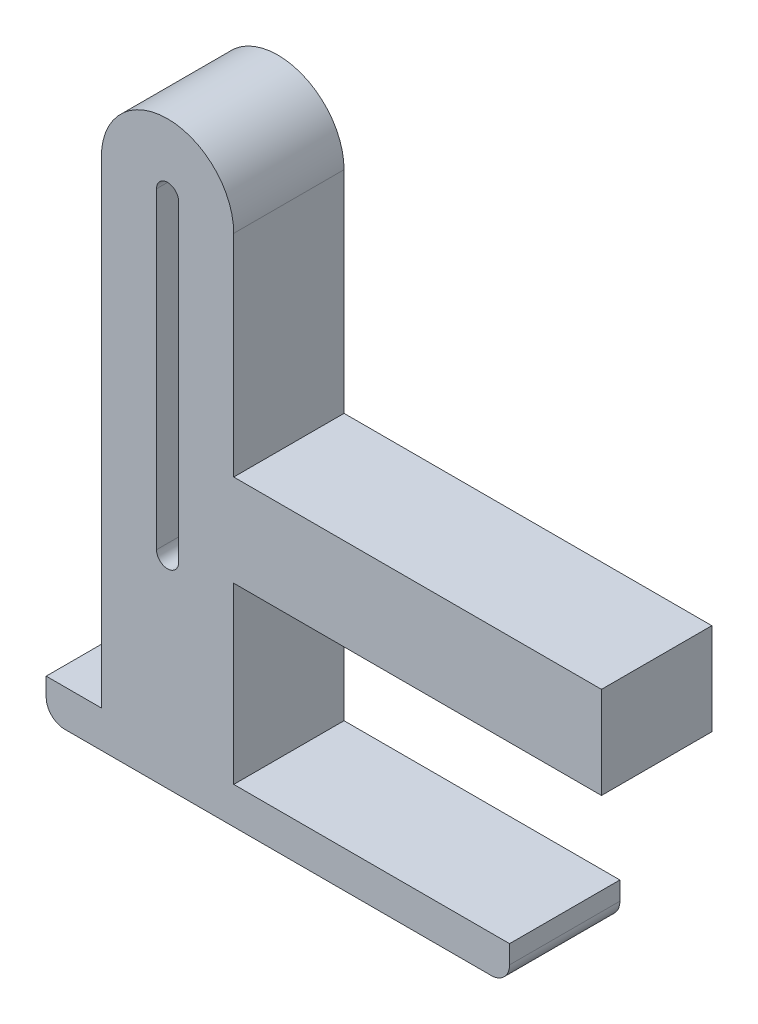
SolidWorks part; units mm, degrees
ref_plane "Front Plane" through (0, 0, 0) normal (0, 0, 1) x (1, 0, 0)
ref_plane "Top Plane" through (0, 0, 0) normal (0, 1, 0) x (1, 0, 0)
ref_plane "Right Plane" through (0, 0, 0) normal (1, 0, 0) x (0, 0, -1)
sketch "Sketch1" plane through (0, 0, 0) normal (0, 0, 1) x (1, 0, 0)
  line L0 (0, 0) -> (0, 17) construction
  line L1 (-0.6, 0) -> (-0.6, 17)
  line L2 (0.6, 0) -> (0.6, 17)
  line L3 (-3.6, 0) -> (-3.6, 17)
  line L4 (3.6, 0) -> (3.6, 17)
  line L5 (-3.6, 0) -> (3.6, 0) construction
  line L6 (3.6, 0) -> (3.6, -10.9543)
  line L7 (3.6, -10.9543) -> (-3.6, -10.9543)
  line L8 (-3.6, -10.9543) -> (-3.6, 0)
  arc A0 (-0.6, 0) -> (0.6, 0) centre (0, 0) ccw
  arc A1 (0.6, 17) -> (-0.6, 17) centre (0, 17) ccw
  arc A2 (3.6, 17) -> (-3.6, 17) centre (0, 17) ccw
  point P2 (0, 8.5)
  dimension "D2" = 10.9543
  dimension "D3" = 3.6
  dimension "D5" = 0.6
  dimension "D1" = 3
  dimension "D4" = 17
extrude "Boss-Extrude1" add sketch "Sketch1" along normal blind 6
sketch "Sketch2" plane through (3.6, 0, 0) normal (1, 0, 0) x (0, 0, -1)
  line L0 (-3, 17) -> (-3, -10.9543) construction
  line L1 (-6, 17) -> (0, 17) construction
  line L3 (-6, 3.0228) -> (0, 3.0228) construction
  line L4 (-6, -10.9543) -> (-6, 17) construction
  line L5 (0, -10.9543) -> (0, 17) construction
  line L6 (-6, -10.9543) -> (0, -10.9543) construction
  line L7 (-6, 0.5228) -> (0, 0.5228)
  line L8 (-6, 0.5228) -> (-6, 5.5228)
  line L9 (-6, 5.5228) -> (0, 5.5228)
  line L10 (0, 0.5228) -> (0, 5.5228)
  line L11 (-6, 0.5228) -> (0, 5.5228) construction
  line L12 (-6, 5.5228) -> (0, 0.5228) construction
  point P12 (-3, 3.0228)
  dimension "D1" = 5
extrude "Boss-Extrude2" add sketch "Sketch2" along normal blind 20
sketch "Эскиз1" plane through (0, 5.5228, 0) normal (0, 1, 0) x (1, 0, 0)
  line L0 (23.6, -3) -> (3.6, -3) construction
  line L1 (23.6, 0) -> (23.6, -6) construction
  line L2 (3.6, 0) -> (3.6, -6) construction
  line L3 (13.6, 0) -> (13.6, -6) construction
  line L4 (23.6, 0) -> (3.6, 0) construction
  line L5 (23.6, -6) -> (3.6, -6) construction
  dimension "D1" = 10
sketch "Эскиз2" plane through (3.6, 0, 0) normal (1, 0, 0) x (0, 0, -1)
  line L0 (-6, -10.9543) -> (-6, 0.5228) construction
  line L1 (-6, -8.9543) -> (0, -8.9543)
  line L2 (-6, -8.9543) -> (-6, -10.9543)
  line L3 (-6, -10.9543) -> (0, -10.9543)
  line L4 (0, -8.9543) -> (0, -10.9543)
  dimension "D1" = 2
extrude "Бобышка-Вытянуть1" add sketch "Эскиз2" along normal blind 15 and the other way blind 10.2
fillet "Скругление3" radius 1 2 edges at (18.6, -10.9543, 3) (-6.6, -10.9543, 3)
